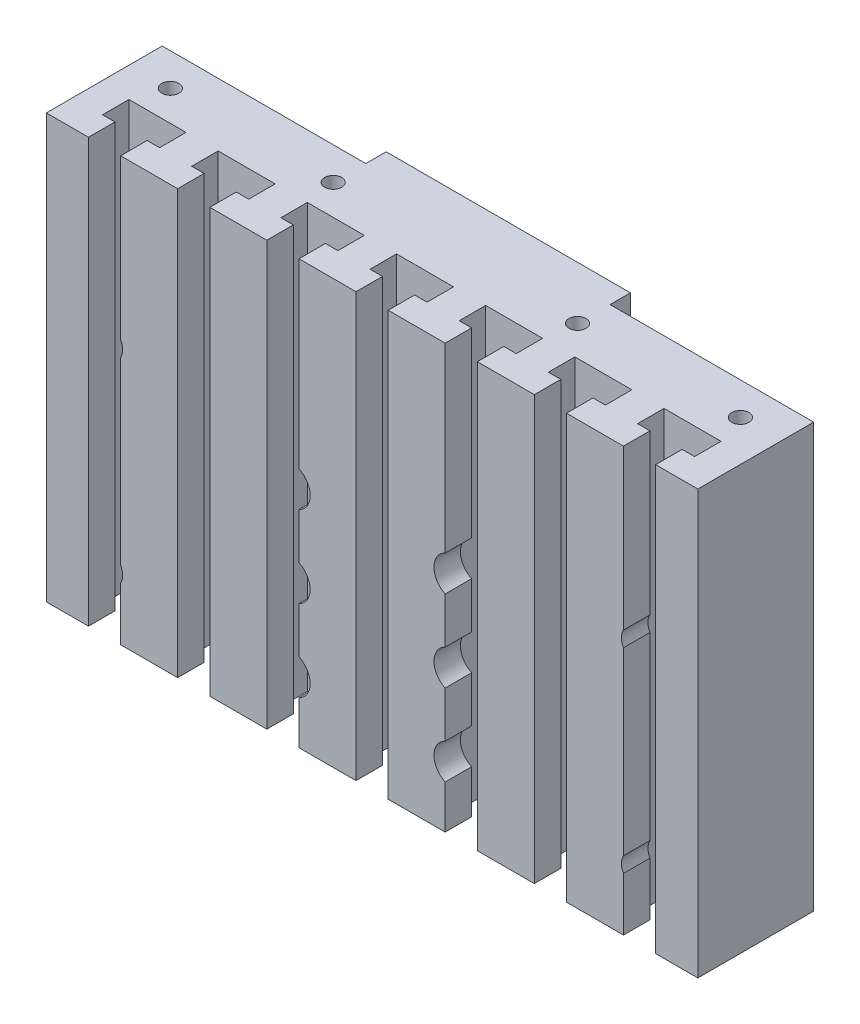
SolidWorks part; units mm, degrees
ref_plane "Front Plane" through (0, 0, 0) normal (0, 0, 1) x (1, 0, 0)
ref_plane "Top Plane" through (0, 0, 0) normal (0, 1, 0) x (1, 0, 0)
ref_plane "Right Plane" through (0, 0, 0) normal (1, 0, 0) x (0, 0, -1)
sketch "Sketch1" plane through (0, 0, 0) normal (0, 0, 1) x (1, 0, 0)
  line L0 (0, 52) -> (0, -52) construction
  line L1 (-80, 52) -> (80, 52)
  line L2 (-80, 52) -> (-80, -52)
  line L3 (-80, -52) -> (80, -52)
  line L4 (80, 52) -> (80, -52)
  line L5 (-80, 52) -> (80, -52) construction
  line L6 (-80, -52) -> (80, 52) construction
  line L7 (20, 52) -> (20, -55.7258) construction
  circle A0 centre (20, -37) radius 2.5
  circle A1 centre (-20, -37) radius 2.5
  circle A2 centre (20, -17) radius 2.5
  circle A3 centre (20, 3) radius 2.5
  circle A4 centre (-20, 3) radius 2.5
  circle A5 centre (-20, -17) radius 2.5
  point P0 (0, 0)
  dimension "D4" = 5
  dimension "D1" = 160
  dimension "D2" = 104
  dimension "D3" = 40
  dimension "D5" = 15
  dimension "D6" = 20
  dimension "D7" = 20
extrude "Boss-Extrude1" add sketch "Sketch1" along normal blind 28.45
sketch "Sketch2" plane through (0, 52, 0) normal (0, 1, 0) x (1, 0, 0)
  line L0 (80, -28.45) -> (-80, -28.45) construction
  line L1 (-3.95, -28.45) -> (3.95, -28.45)
  line L2 (-3.95, -28.45) -> (-3.95, -21.95)
  line L4 (3.95, -28.45) -> (3.95, -21.95)
  line L5 (3.95, -21.95) -> (7, -21.95)
  line L6 (-7, -15.45) -> (7, -15.45)
  line L7 (-7, -15.45) -> (-7, -21.95)
  line L8 (-7, -21.95) -> (-3.95, -21.95)
  line L9 (7, -15.45) -> (7, -21.95)
  line L10 (0, 0) -> (0, -28.45) construction
  line L11 (80, 0) -> (-80, 0) construction
  line L12 (25.85, -28.45) -> (25.85, -21.95)
  line L13 (17.95, -28.45) -> (25.85, -28.45)
  line L14 (25.85, -21.95) -> (28.9, -21.95)
  line L15 (28.9, -15.45) -> (28.9, -21.95)
  line L16 (14.9, -15.45) -> (28.9, -15.45)
  line L17 (14.9, -15.45) -> (14.9, -21.95)
  line L18 (14.9, -21.95) -> (17.95, -21.95)
  line L19 (17.95, -28.45) -> (17.95, -21.95)
  line L20 (47.75, -28.45) -> (47.75, -21.95)
  line L21 (39.85, -28.45) -> (47.75, -28.45)
  line L22 (47.75, -21.95) -> (50.8, -21.95)
  line L23 (50.8, -15.45) -> (50.8, -21.95)
  line L24 (36.8, -15.45) -> (50.8, -15.45)
  line L25 (36.8, -15.45) -> (36.8, -21.95)
  line L26 (36.8, -21.95) -> (39.85, -21.95)
  line L27 (39.85, -28.45) -> (39.85, -21.95)
  line L28 (69.65, -28.45) -> (69.65, -21.95)
  line L29 (61.75, -28.45) -> (69.65, -28.45)
  line L30 (69.65, -21.95) -> (72.7, -21.95)
  line L31 (72.7, -15.45) -> (72.7, -21.95)
  line L32 (58.7, -15.45) -> (72.7, -15.45)
  line L33 (58.7, -15.45) -> (58.7, -21.95)
  line L34 (58.7, -21.95) -> (61.75, -21.95)
  line L35 (61.75, -28.45) -> (61.75, -21.95)
  line L36 (-28.9, -15.45) -> (-28.9, -21.95)
  line L37 (-28.9, -21.95) -> (-25.85, -21.95)
  line L38 (-25.85, -28.45) -> (-25.85, -21.95)
  line L39 (-28.9, -15.45) -> (-14.9, -15.45)
  line L40 (-14.9, -15.45) -> (-14.9, -21.95)
  line L41 (-17.95, -28.45) -> (-17.95, -21.95)
  line L42 (-25.85, -28.45) -> (-17.95, -28.45)
  line L43 (-17.95, -21.95) -> (-14.9, -21.95)
  line L44 (-50.8, -15.45) -> (-50.8, -21.95)
  line L45 (-50.8, -21.95) -> (-47.75, -21.95)
  line L46 (-47.75, -28.45) -> (-47.75, -21.95)
  line L47 (-50.8, -15.45) -> (-36.8, -15.45)
  line L48 (-36.8, -15.45) -> (-36.8, -21.95)
  line L49 (-39.85, -28.45) -> (-39.85, -21.95)
  line L50 (-47.75, -28.45) -> (-39.85, -28.45)
  line L51 (-39.85, -21.95) -> (-36.8, -21.95)
  line L52 (-72.7, -15.45) -> (-72.7, -21.95)
  line L53 (-72.7, -21.95) -> (-69.65, -21.95)
  line L54 (-69.65, -28.45) -> (-69.65, -21.95)
  line L55 (-72.7, -15.45) -> (-58.7, -15.45)
  line L56 (-58.7, -15.45) -> (-58.7, -21.95)
  line L57 (-61.75, -28.45) -> (-61.75, -21.95)
  line L58 (-69.65, -28.45) -> (-61.75, -28.45)
  line L59 (-61.75, -21.95) -> (-58.7, -21.95)
  point P14 (0, -15.45)
  dimension "D1" = 14
  dimension "D2" = 7.9
  dimension "D3" = 6.5
  dimension "D4" = 6.5
  dimension "D6" = 7.9
  dimension "D8" = 7.9
  dimension "D5" = 4
  dimension "D7" = 4
extrude "Cut-Extrude1" cut sketch "Sketch2" against normal through all
sketch "Sketch5" plane through (0, 0, 0) normal (0, 0, -1) x (-1, 0, 0)
  line L0 (0, 52) -> (0, -52) construction
  line L1 (-80, 52) -> (80, 52) construction
  line L2 (80, -52) -> (-80, -52) construction
  line L4 (-30, -52) -> (30, -52)
  line L5 (-30, -52) -> (-30, 52)
  line L6 (-30, 52) -> (30, 52)
  line L7 (30, -52) -> (30, 52)
  point P10 (0, 52)
  dimension "D1" = 60
extrude "Boss-Extrude2" add sketch "Sketch5" along normal blind 5
sketch "Sketch3" plane through (0, 0, 28.45) normal (0, 0, 1) x (1, 0, 0)
  circle A0 centre (-20, 3) radius 4.8
  circle A1 centre (20, 3) radius 4.8
  circle A2 centre (-20, -17) radius 4.8
  circle A3 centre (20, -17) radius 4.8
  circle A4 centre (-20, -37) radius 4.8
  circle A5 centre (20, -37) radius 4.8
  dimension "D1" = 9.6
extrude "Cut-Extrude2" cut sketch "Sketch3" against normal blind 7
sketch "Sketch4" plane through (0, 0, 15.45) normal (0, 0, 1) x (1, 0, 0)
  circle A0 centre (-20, 3) radius 4.8
  circle A1 centre (20, 3) radius 4.8
  circle A2 centre (-20, -17) radius 4.8
  circle A3 centre (20, -17) radius 4.8
  circle A4 centre (-20, -37) radius 4.8
  circle A5 centre (20, -37) radius 4.8
  dimension "D1" = 9.6
extrude "Cut-Extrude3" cut sketch "Sketch4" against normal blind 13.35 from surface at 6.5 starting at face at (-16.515, -10.2, 21.95)
sketch "Sketch6" plane through (0, 0, 0) normal (0, 0, 1) x (1, 0, 0)
  circle A0 centre (-20, 3) radius 2.5
  circle A1 centre (20, 3) radius 2.5
  circle A2 centre (-20, -17) radius 2.5
  circle A3 centre (20, -17) radius 2.5
  circle A4 centre (20, -37) radius 2.5
  circle A5 centre (-20, -37) radius 2.5
  dimension "D1" = 5
extrude "Cut-Extrude4" cut sketch "Sketch6" against normal through all
sketch "Sketch7" plane through (0, 52, 0) normal (0, 1, 0) x (1, 0, 0)
  line L0 (-80, -8) -> (80, -8) construction
  line L1 (-80, -28.45) -> (-80, 0) construction
  line L2 (80, -28.45) -> (80, 0) construction
  line L4 (-30, 0) -> (-80, 0) construction
  line L6 (0, 5) -> (0, -15.45) construction
  line L7 (-30, 5) -> (30, 5) construction
  line L8 (7, -15.45) -> (-7, -15.45) construction
  circle A0 centre (-70, -8) radius 2.1
  circle A1 centre (-30, -8) radius 2.1
  circle A2 centre (70, -8) radius 2.1
  circle A3 centre (30, -8) radius 2.1
  dimension "D1" = 4.2
  dimension "D3" = 40
  dimension "D2" = 10
  dimension "D4" = 8
extrude "Cut-Extrude5" cut sketch "Sketch7" against normal blind 12
sketch "Sketch8" plane through (0, -52, 0) normal (0, -1, 0) x (1, 0, 0)
  line L0 (80, 8) -> (-80, 8) construction
  line L1 (80, 28.45) -> (80, 0) construction
  line L2 (-80, 28.45) -> (-80, 0) construction
  line L3 (30, 0) -> (80, 0) construction
  line L6 (0, -5) -> (0, 15.45) construction
  line L7 (30, -5) -> (-30, -5) construction
  line L8 (7, 15.45) -> (-7, 15.45) construction
  circle A0 centre (70, 8) radius 2.1
  circle A1 centre (30, 8) radius 2.1
  circle A2 centre (-30, 8) radius 2.1
  circle A3 centre (-70, 8) radius 2.1
  dimension "D1" = 4.2
  dimension "D2" = 10
  dimension "D3" = 40
  dimension "D4" = 8
extrude "Cut-Extrude6" cut sketch "Sketch8" against normal blind 12
sketch "Sketch9" plane through (0, 0, 28.45) normal (0, 0, 1) x (1, 0, 0)
  line L0 (0, 47.1529) -> (0, -45.7832) construction
  line L1 (-80, -52) -> (-69.65, -52) construction
  line L2 (-65, 11) -> (65, 11) construction
  line L3 (-65, 11) -> (-65, -37) construction
  line L4 (-65, -37) -> (65, -37) construction
  line L5 (65, 11) -> (65, -37) construction
  circle A0 centre (-65, 11) radius 3.75
  circle A1 centre (-65, -37) radius 3.75
  circle A2 centre (65, -37) radius 3.75
  circle A3 centre (65, 11) radius 3.75
  point P3 (0, 11)
  point P8 (-65, -13)
  dimension "D3" = 7.5
  dimension "D1" = 130
  dimension "D2" = 48
  dimension "D4" = 15
extrude "Cut-Extrude7" cut sketch "Sketch9" against normal blind 26
